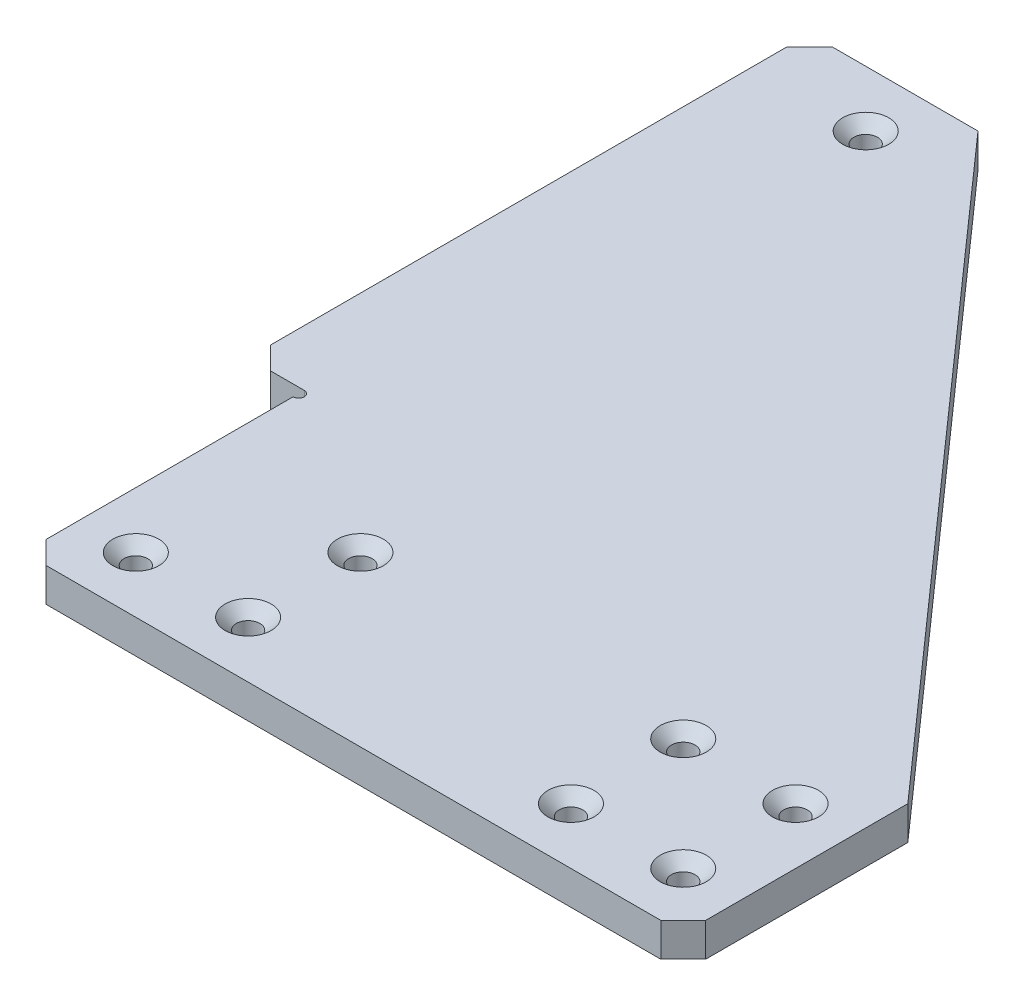
SolidWorks part; units mm, degrees
ref_plane "前视基准面" through (0, 0, 0) normal (0, 0, 1) x (1, 0, 0)
ref_plane "上视基准面" through (0, 0, 0) normal (0, 1, 0) x (1, 0, 0)
ref_plane "右视基准面" through (0, 0, 0) normal (1, 0, 0) x (0, 0, -1)
sketch "草图1" plane through (0, 0, 0) normal (0, 1, 0) x (1, 0, 0)
  line L0 (-68.75, 150) -> (-68.75, 50)
  line L1 (-58.75, 0) -> (58.75, 0)
  line L2 (58.75, 0) -> (58.75, 40)
  line L3 (58.75, 40) -> (-38.75, 150)
  line L4 (-38.75, 150) -> (-68.75, 150)
  line L5 (-48.75, 140) -> (-48.75, 10) construction
  line L6 (48.75, 30) -> (48.75, 10) construction
  line L7 (28.75, 10) -> (-28.75, 10) construction
  line L8 (28.75, 10) -> (28.75, 30) construction
  line L9 (28.75, 30) -> (-28.75, 30) construction
  line L10 (-28.75, 10) -> (-28.75, 30) construction
  line L11 (28.75, 10) -> (-28.75, 30) construction
  line L12 (28.75, 30) -> (-28.75, 10) construction
  line L13 (-68.75, 50) -> (-58.75, 50)
  line L14 (-58.75, 50) -> (-58.75, 0)
  circle A0 centre (-48.75, 140) radius 2.1
  circle A2 centre (-48.75, 10) radius 2.1
  circle A3 centre (-28.75, 30) radius 2.1
  circle A4 centre (28.75, 30) radius 2.1
  circle A5 centre (-28.75, 10) radius 2.1
  circle A6 centre (28.75, 10) radius 2.1
  circle A7 centre (48.75, 30) radius 2.1
  circle A8 centre (48.75, 10) radius 2.1
  point P12 (0, 20)
  dimension "D5" = 4.2
  dimension "D6" = 10
  dimension "D9" = 10
  dimension "D12" = 10
  dimension "D1" = 127.5
  dimension "D2" = 40
  dimension "D3" = 30
  dimension "D4" = 150
  dimension "D7" = 10
  dimension "D8" = 20
  dimension "D10" = 20
  dimension "D11" = 20
  dimension "D13" = 10
  dimension "D14" = 50
extrude "凸台-拉伸1" add sketch "草图1" along normal mid plane 6
sketch "草图2" plane through (0, 3, 0) normal (0, 1, 0) x (1, 0, 0)
  line L0 (-58.75, 50) -> (-58.75, 0) construction
  circle A0 centre (-58.75, 49) radius 1
  dimension "D1" = 2
extrude "切除-拉伸1" cut sketch "草图2" against normal through all
chamfer "倒角1" distance 4 angle 45 4 edges at (-68.75, 0, -150) (58.75, 0, 0) (-58.75, 0, 0) (-68.75, 0, -50)
chamfer "倒角2" distance 2 angle 45 8 edges at (48.75, 3, -7.9) (48.75, 3, -27.9) (28.75, 3, -27.9) (28.75, 3, -7.9) (-48.75, 3, -7.9) (-28.75, 3, -7.9) (-28.75, 3, -27.9) (-48.75, 3, -137.9)
